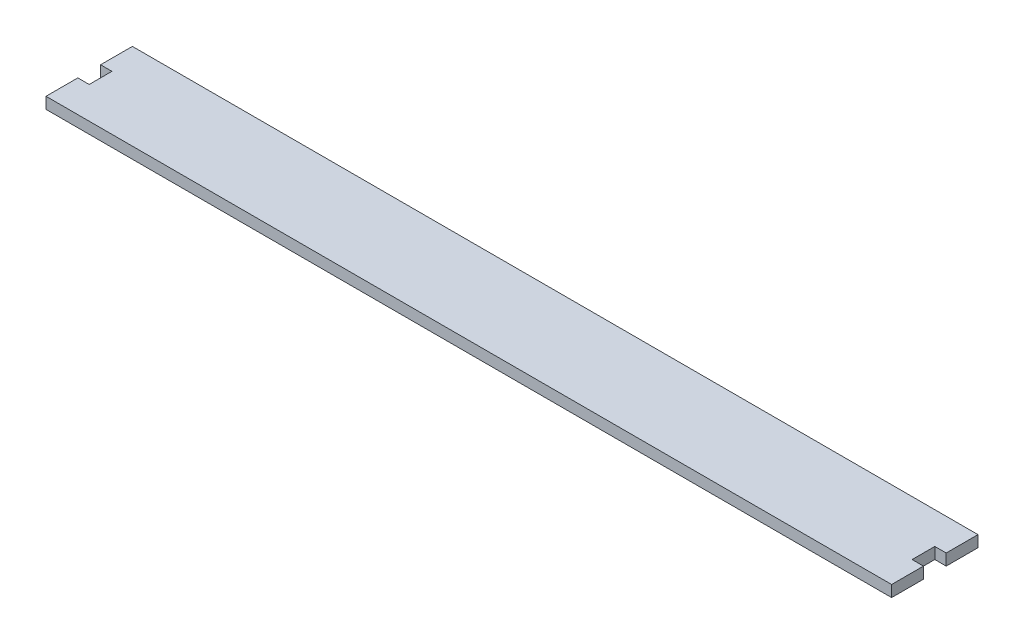
SolidWorks part; units mm, degrees
ref_plane "Front Plane" through (0, 0, 0) normal (0, 0, 1) x (1, 0, 0)
ref_plane "Top Plane" through (0, 0, 0) normal (0, 1, 0) x (1, 0, 0)
ref_plane "Right Plane" through (0, 0, 0) normal (1, 0, 0) x (0, 0, -1)
sketch "Sketch1" plane through (0, 0, 0) normal (0, 1, 0) x (1, 0, 0)
  line L1 (186, 19) -> (-186, 19)
  line L2 (186, 19) -> (186, 5)
  line L3 (186, -19) -> (-186, -19)
  line L4 (-186, 19) -> (-186, 5)
  line L5 (186, 19) -> (-186, -19) construction
  line L6 (186, -19) -> (-186, 19) construction
  line L7 (-181, 5) -> (-181, -5)
  line L8 (-181, 5) -> (-186, 5)
  line L9 (-181, -5) -> (-186, -5)
  line L10 (-186, -5) -> (-186, -19)
  line L11 (181, 5) -> (181, -5)
  line L12 (181, 5) -> (186, 5)
  line L13 (181, -5) -> (186, -5)
  line L14 (186, -5) -> (186, -19)
  point P0 (0, 0)
  dimension "D1" = 372
  dimension "D2" = 38
  dimension "D3" = 5
  dimension "D4" = 10
  dimension "D5" = 5
  dimension "D6" = 10
extrude "Boss-Extrude1" add sketch "Sketch1" along normal blind 5
